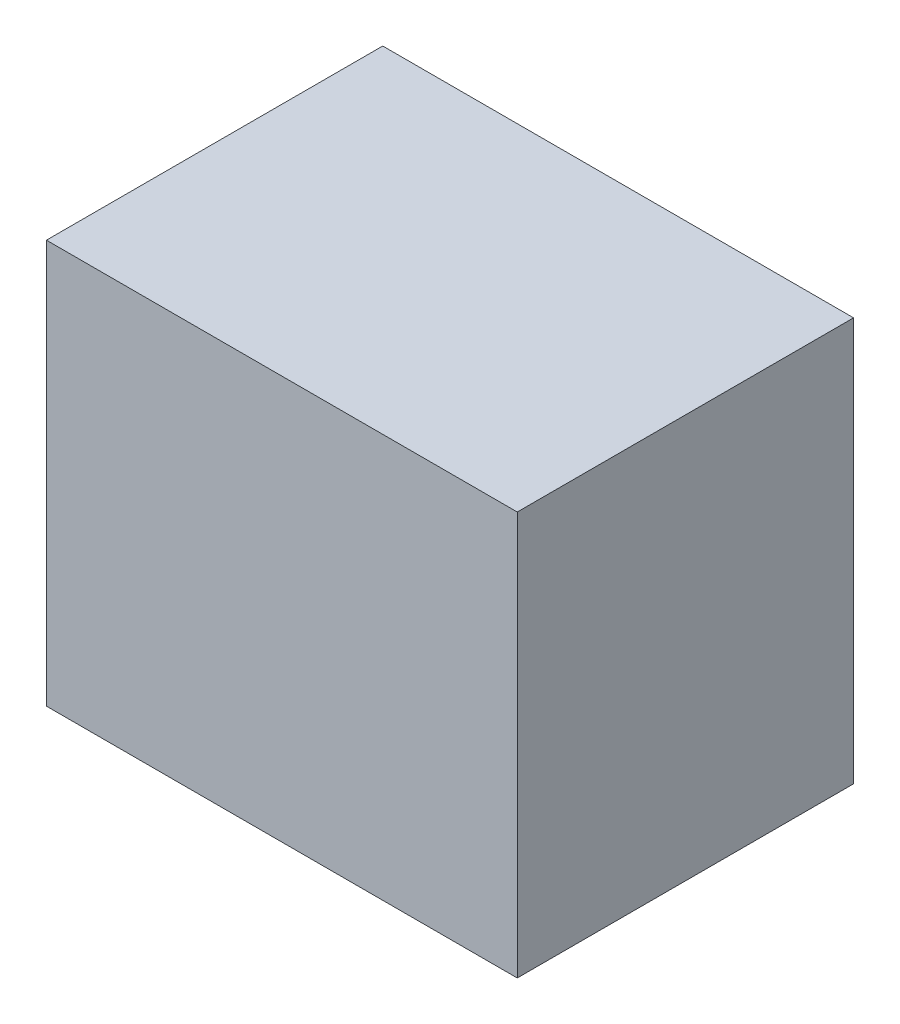
SolidWorks part; units mm, degrees
ref_plane "Front Plane" through (0, 0, 0) normal (0, 0, 1) x (1, 0, 0)
ref_plane "Top Plane" through (0, 0, 0) normal (0, 1, 0) x (1, 0, 0)
ref_plane "Right Plane" through (0, 0, 0) normal (1, 0, 0) x (0, 0, -1)
sketch "Sketch1" plane through (0, 0, 0) normal (0, 0, 1) x (1, 0, 0)
  line L0 (-78.7496, 0) -> (58.3509, 0) construction
  line L1 (35, 30) -> (-35, 30)
  line L2 (35, 30) -> (35, -30)
  line L3 (35, -30) -> (-35, -30)
  line L4 (-35, 30) -> (-35, -30)
  line L5 (35, 30) -> (-35, -30) construction
  line L6 (35, -30) -> (-35, 30) construction
  point P2 (0, 0)
  dimension "D1" = 70
  dimension "D2" = 60
extrude "Boss-Extrude1" add sketch "Sketch1" along normal blind 50
